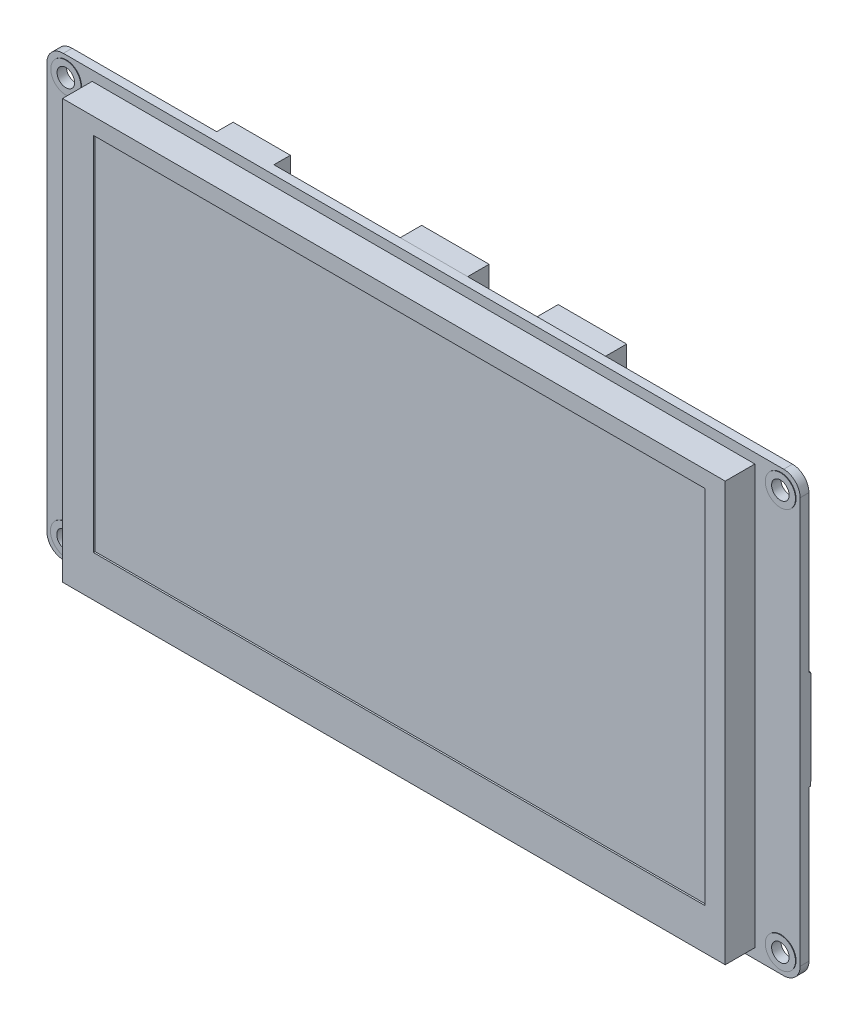
SolidWorks part; units mm, degrees
material "Plastique personnalisé"
ref_plane "Plan de face" through (0, 0, 0) normal (0, 0, 1) x (1, 0, 0)
ref_plane "Plan de dessus" through (0, 0, 0) normal (0, 1, 0) x (1, 0, 0)
ref_plane "Plan de droite" through (0, 0, 0) normal (1, 0, 0) x (0, 0, -1)
sketch "Esquisse1" plane through (0, 0, 0) normal (0, 0, 1) x (1, 0, 0)
  line L1 (-65.6, -39.95) -> (65.6, -39.95)
  line L2 (-68.6, -36.95) -> (-68.6, 36.95)
  line L3 (-65.6, 39.95) -> (65.6, 39.95)
  line L4 (68.6, -36.95) -> (68.6, 36.95)
  line L5 (-68.6, -39.95) -> (68.6, 39.95) construction
  line L6 (-68.6, 39.95) -> (68.6, -39.95) construction
  line L11 (-65.1, -36.45) -> (65.1, 36.45) construction
  line L12 (-65.1, 36.45) -> (65.1, -36.45) construction
  arc A0 (-68.6, 36.95) -> (-65.6, 39.95) centre (-65.6, 36.95) cw
  arc A1 (-65.6, -39.95) -> (-68.6, -36.95) centre (-65.6, -36.95) cw
  arc A2 (65.6, -39.95) -> (68.6, -36.95) centre (65.6, -36.95) ccw
  arc A3 (65.6, 39.95) -> (68.6, 36.95) centre (65.6, 36.95) cw
  circle A4 centre (-65.043, 36.45) radius 1.6
  circle A5 centre (65.1, 36.45) radius 1.6
  circle A6 centre (65.1, -36.45) radius 1.6
  circle A7 centre (-65.1, -36.45) radius 1.6
  point P0 (0, 0)
  point P18 (0, 0)
  dimension "D3" = 3
  dimension "D6" = 3.2
  dimension "D7" = 3.2
  dimension "D8" = 3.2
  dimension "D1" = 137.2
  dimension "D2" = 79.9
  dimension "D4" = 130.2
  dimension "D5" = 72.9
sketch "dalle ecran" plane through (0, 0, 0) normal (0, 0, 1) x (1, 0, 0)
  line L1 (-60.35, -38.15) -> (60.35, -38.15)
  line L2 (-60.35, -38.15) -> (-60.35, 38.15)
  line L3 (-60.35, 38.15) -> (60.35, 38.15)
  line L4 (60.35, -38.15) -> (60.35, 38.15)
  line L5 (-60.35, -38.15) -> (60.35, 38.15) construction
  line L6 (-60.35, 38.15) -> (60.35, -38.15) construction
  point P0 (0, 0)
  dimension "D1" = 120.7
  dimension "D2" = 76.3
extrude "Boss.-Extru.1" add sketch "Esquisse1" against normal blind 1.6
sketch "Esquisse4" plane through (0, 0, 0) normal (0, 0, 1) x (1, 0, 0)
  circle A0 centre (-65.043, 36.45) radius 1.6
  circle A1 centre (-65.043, 36.45) radius 2.7455
  circle A2 centre (65.1, 36.45) radius 1.6
  circle A3 centre (65.1, 36.45) radius 2.7533
  circle A4 centre (-65.1, -36.45) radius 1.6
  circle A5 centre (-65.1, -36.45) radius 2.7486
  circle A7 centre (65.1, -36.45) radius 2.7491
  circle A8 centre (65.1, -36.45) radius 1.6
extrude "Boss.-Extru.2" add sketch "Esquisse4" along normal blind 0.1
extrude "Boss.-Extru.3" add sketch "dalle ecran" along normal blind 5.4
sketch "Esquisse5" plane through (0, 0, 5.4) normal (0, 0, 1) x (1, 0, 0)
  line L0 (-60.35, 0) -> (-54.7003, 0) construction
  line L1 (-60.35, 38.15) -> (-60.35, -38.15) construction
  line L2 (0, -38.15) -> (0, -30.6518) construction
  line L3 (-60.35, -38.15) -> (60.35, -38.15) construction
  line L4 (0, -30.6518) -> (-54.7003, -30.6518) construction
  line L5 (0, 38.15) -> (0, 35.148) construction
  line L6 (60.35, 38.15) -> (-60.35, 38.15) construction
  line L7 (0, 35.148) -> (-54.7003, 35.148) construction
  line L8 (-54.7003, 0) -> (60.35, 0) construction
  line L9 (60.35, -38.15) -> (60.35, 38.15) construction
  line L10 (60.35, 0) -> (56.695, 0) construction
  line L11 (56.695, 0) -> (56.695, 35.148) construction
  line L13 (56.695, 35.148) -> (-54.7003, 35.148)
  line L14 (56.695, 35.148) -> (56.695, -30.6518)
  line L15 (56.695, -30.6518) -> (-54.7003, -30.6518)
  line L16 (-54.7003, 35.148) -> (-54.7003, -30.6518)
  dimension "D1" = 5.6497
extrude "Enlèv. mat.-Extru.1" cut sketch "Esquisse5" against normal blind 0.3
sketch "sd-card" plane through (0, 0, -1.6) normal (0, 0, -1) x (-1, 0, 0)
  line L0 (0, 0) -> (68.6, 0) construction
  line L1 (68.6, 36.95) -> (68.6, -36.95) construction
  line L2 (126.6709, 304.2897) -> (905.3376, 304.2897) construction
  line L4 (39.2733, -25.2253) -> (54.2505, -25.2253)
  line L5 (39.2733, -25.2253) -> (39.2733, -39.1139)
  line L6 (39.2733, -39.1139) -> (54.2505, -39.1139)
  line L7 (54.2505, -25.2253) -> (54.2505, -39.1139)
sketch "embase esp32S3" plane through (0, 0, -1.6) normal (0, 0, -1) x (-1, 0, 0)
  line L0 (-68.6, -36.95) -> (-68.6, 36.95) construction
  line L1 (-68.6, 8.5181) -> (-61.4864, 8.5181)
  line L2 (-68.6, 8.5181) -> (-68.6, -9.4826)
  line L3 (-68.6, -9.4826) -> (-61.3564, -9.4826)
  line L4 (-42.8193, 8.5181) -> (-42.8193, 6.945)
  line L5 (-60.2164, 9.3816) -> (-60.2164, 8.5181)
  line L6 (-61.4864, 9.3816) -> (-60.4586, 9.3816)
  line L7 (-61.4864, 9.3816) -> (-61.4864, 8.5181)
  line L9 (-60.4586, 9.3816) -> (-60.4586, 8.5181)
  line L10 (-60.2164, 9.3816) -> (-59.1886, 9.3816)
  line L11 (-59.1886, 9.3816) -> (-59.1886, 8.5181)
  line L13 (-58.9464, 9.3816) -> (-58.9464, 8.5181)
  line L14 (-58.9464, 9.3816) -> (-57.9186, 9.3816)
  line L15 (-57.9186, 9.3816) -> (-57.9186, 8.5181)
  line L17 (-57.6764, 9.3816) -> (-57.6764, 8.5181)
  line L18 (-57.6764, 9.3816) -> (-56.6486, 9.3816)
  line L19 (-56.6486, 9.3816) -> (-56.6486, 8.5181)
  line L21 (-56.4064, 9.3816) -> (-56.4064, 8.5181)
  line L22 (-56.4064, 9.3816) -> (-55.3786, 9.3816)
  line L23 (-55.3786, 9.3816) -> (-55.3786, 8.5181)
  line L25 (-55.1364, 9.3816) -> (-55.1364, 8.5181)
  line L26 (-55.1364, 9.3816) -> (-54.1086, 9.3816)
  line L27 (-54.1086, 9.3816) -> (-54.1086, 8.5181)
  line L29 (-53.8664, 9.3816) -> (-53.8664, 8.5181)
  line L30 (-53.8664, 9.3816) -> (-52.8386, 9.3816)
  line L31 (-52.8386, 9.3816) -> (-52.8386, 8.5181)
  line L33 (-52.5964, 9.3816) -> (-52.5964, 8.5181)
  line L34 (-52.5964, 9.3816) -> (-51.5686, 9.3816)
  line L35 (-51.5686, 9.3816) -> (-51.5686, 8.5181)
  line L37 (-51.3264, 9.3816) -> (-51.3264, 8.5181)
  line L38 (-51.3264, 9.3816) -> (-50.2986, 9.3816)
  line L39 (-50.2986, 9.3816) -> (-50.2986, 8.5181)
  line L41 (-50.0564, 9.3816) -> (-50.0564, 8.5181)
  line L42 (-50.0564, 9.3816) -> (-49.0286, 9.3816)
  line L43 (-49.0286, 9.3816) -> (-49.0286, 8.5181)
  line L45 (-48.7864, 9.3816) -> (-48.7864, 8.5181)
  line L46 (-48.7864, 9.3816) -> (-47.7586, 9.3816)
  line L47 (-47.7586, 9.3816) -> (-47.7586, 8.5181)
  line L49 (-47.5164, 9.3816) -> (-47.5164, 8.5181)
  line L50 (-47.5164, 9.3816) -> (-46.4886, 9.3816)
  line L51 (-46.4886, 9.3816) -> (-46.4886, 8.5181)
  line L53 (-46.2464, 9.3816) -> (-46.2464, 8.5181)
  line L54 (-46.2464, 9.3816) -> (-45.2186, 9.3816)
  line L55 (-45.2186, 9.3816) -> (-45.2186, 8.5181)
  line L57 (-44.9764, 9.3816) -> (-44.9764, 8.5181)
  line L58 (-44.9764, 9.3816) -> (-43.9486, 9.3816)
  line L59 (-43.9486, 9.3816) -> (-43.9486, 8.5181)
  line L61 (-60.4586, 8.5181) -> (-60.2164, 8.5181)
  line L62 (-59.1886, 8.5181) -> (-58.9464, 8.5181)
  line L63 (-57.9186, 8.5181) -> (-57.6764, 8.5181)
  line L64 (-56.6486, 8.5181) -> (-56.4064, 8.5181)
  line L65 (-55.3786, 8.5181) -> (-55.1364, 8.5181)
  line L66 (-54.1086, 8.5181) -> (-53.8664, 8.5181)
  line L67 (-52.8386, 8.5181) -> (-52.5964, 8.5181)
  line L68 (-51.5686, 8.5181) -> (-51.3264, 8.5181)
  line L69 (-50.2986, 8.5181) -> (-50.0564, 8.5181)
  line L70 (-49.0286, 8.5181) -> (-48.7864, 8.5181)
  line L71 (-47.7586, 8.5181) -> (-47.5164, 8.5181)
  line L72 (-46.4886, 8.5181) -> (-46.2464, 8.5181)
  line L73 (-45.2186, 8.5181) -> (-44.9764, 8.5181)
  line L74 (-43.9486, 8.5181) -> (-42.8193, 8.5181)
  line L88 (-42.8193, 5.675) -> (-42.0215, 5.675)
  line L89 (-42.8193, 6.945) -> (-42.0215, 6.945)
  line L91 (-42.8193, 6.1624) -> (-42.0215, 6.1624)
  line L92 (-42.0215, 6.945) -> (-42.0215, 6.1624)
  line L93 (-42.0215, 5.675) -> (-42.0215, 4.8924)
  line L94 (-42.8193, 4.8924) -> (-42.0215, 4.8924)
  line L96 (-42.8193, 4.405) -> (-42.0215, 4.405)
  line L97 (-42.0215, 4.405) -> (-42.0215, 3.6224)
  line L98 (-42.8193, 3.6224) -> (-42.0215, 3.6224)
  line L100 (-42.8193, 3.135) -> (-42.0215, 3.135)
  line L101 (-42.0215, 3.135) -> (-42.0215, 2.3524)
  line L102 (-42.8193, 2.3524) -> (-42.0215, 2.3524)
  line L104 (-42.8193, 1.865) -> (-42.0215, 1.865)
  line L105 (-42.0215, 1.865) -> (-42.0215, 1.0824)
  line L106 (-42.8193, 1.0824) -> (-42.0215, 1.0824)
  line L108 (-42.8193, 0.595) -> (-42.0215, 0.595)
  line L109 (-42.0215, 0.595) -> (-42.0215, -0.1876)
  line L110 (-42.8193, -0.1876) -> (-42.0215, -0.1876)
  line L112 (-42.8193, -0.675) -> (-42.0215, -0.675)
  line L113 (-42.0215, -0.675) -> (-42.0215, -1.4576)
  line L114 (-42.8193, -1.4576) -> (-42.0215, -1.4576)
  line L116 (-42.8193, -1.945) -> (-42.0215, -1.945)
  line L117 (-42.0215, -1.945) -> (-42.0215, -2.7276)
  line L118 (-42.8193, -2.7276) -> (-42.0215, -2.7276)
  line L120 (-42.8193, -3.215) -> (-42.0215, -3.215)
  line L121 (-42.0215, -3.215) -> (-42.0215, -3.9976)
  line L122 (-42.8193, -3.9976) -> (-42.0215, -3.9976)
  line L124 (-42.8193, -4.485) -> (-42.0215, -4.485)
  line L125 (-42.0215, -4.485) -> (-42.0215, -5.2676)
  line L126 (-42.8193, -5.2676) -> (-42.0215, -5.2676)
  line L128 (-42.8193, -5.755) -> (-42.0215, -5.755)
  line L129 (-42.0215, -5.755) -> (-42.0215, -6.5376)
  line L130 (-42.8193, -6.5376) -> (-42.0215, -6.5376)
  line L132 (-42.8193, -7.025) -> (-42.0215, -7.025)
  line L133 (-42.0215, -7.025) -> (-42.0215, -7.8076)
  line L134 (-42.8193, -7.8076) -> (-42.0215, -7.8076)
  line L136 (-42.8193, 6.1624) -> (-42.8193, 5.675)
  line L137 (-42.8193, 4.8924) -> (-42.8193, 4.405)
  line L138 (-42.8193, 3.6224) -> (-42.8193, 3.135)
  line L139 (-42.8193, 2.3524) -> (-42.8193, 1.865)
  line L140 (-42.8193, 1.0824) -> (-42.8193, 0.595)
  line L141 (-42.8193, -0.1876) -> (-42.8193, -0.675)
  line L142 (-42.8193, -1.4576) -> (-42.8193, -1.945)
  line L143 (-42.8193, -2.7276) -> (-42.8193, -3.215)
  line L144 (-42.8193, -3.9976) -> (-42.8193, -4.485)
  line L145 (-42.8193, -5.2676) -> (-42.8193, -5.755)
  line L146 (-42.8193, -6.5376) -> (-42.8193, -7.025)
  line L147 (-42.8193, -7.8076) -> (-42.8193, -9.4826)
  line L148 (-46.1164, -9.4826) -> (-46.1164, -10.3789)
  line L150 (-44.8464, -9.4826) -> (-44.8464, -10.3789)
  line L151 (-44.8464, -10.3789) -> (-43.9768, -10.3789)
  line L152 (-43.9768, -9.4826) -> (-43.9768, -10.3789)
  line L154 (-45.2468, -9.4826) -> (-45.2468, -10.3789)
  line L155 (-46.1164, -10.3789) -> (-45.2468, -10.3789)
  line L156 (-47.3864, -9.4826) -> (-47.3864, -10.3789)
  line L158 (-46.5168, -9.4826) -> (-46.5168, -10.3789)
  line L159 (-47.3864, -10.3789) -> (-46.5168, -10.3789)
  line L160 (-48.6564, -9.4826) -> (-48.6564, -10.3789)
  line L161 (-48.6564, -9.4826) -> (-47.7868, -9.4826)
  line L162 (-47.7868, -9.4826) -> (-47.7868, -10.3789)
  line L163 (-48.6564, -10.3789) -> (-47.7868, -10.3789)
  line L164 (-49.9264, -9.4826) -> (-49.9264, -10.3789)
  line L166 (-49.0568, -9.4826) -> (-49.0568, -10.3789)
  line L167 (-49.9264, -10.3789) -> (-49.0568, -10.3789)
  line L168 (-51.1964, -9.4826) -> (-51.1964, -10.3789)
  line L170 (-50.3268, -9.4826) -> (-50.3268, -10.3789)
  line L171 (-51.1964, -10.3789) -> (-50.3268, -10.3789)
  line L172 (-52.4664, -9.4826) -> (-52.4664, -10.3789)
  line L174 (-51.5968, -9.4826) -> (-51.5968, -10.3789)
  line L175 (-52.4664, -10.3789) -> (-51.5968, -10.3789)
  line L176 (-53.7364, -9.4826) -> (-53.7364, -10.3789)
  line L178 (-52.8668, -9.4826) -> (-52.8668, -10.3789)
  line L179 (-53.7364, -10.3789) -> (-52.8668, -10.3789)
  line L180 (-55.0064, -9.4826) -> (-55.0064, -10.3789)
  line L182 (-54.1368, -9.4826) -> (-54.1368, -10.3789)
  line L183 (-55.0064, -10.3789) -> (-54.1368, -10.3789)
  line L184 (-56.2764, -9.4826) -> (-56.2764, -10.3789)
  line L186 (-55.4068, -9.4826) -> (-55.4068, -10.3789)
  line L187 (-56.2764, -10.3789) -> (-55.4068, -10.3789)
  line L188 (-57.5464, -9.4826) -> (-57.5464, -10.3789)
  line L190 (-56.6768, -9.4826) -> (-56.6768, -10.3789)
  line L191 (-57.5464, -10.3789) -> (-56.6768, -10.3789)
  line L192 (-58.8164, -9.4826) -> (-58.8164, -10.3789)
  line L194 (-57.9468, -9.4826) -> (-57.9468, -10.3789)
  line L195 (-58.8164, -10.3789) -> (-57.9468, -10.3789)
  line L196 (-60.0864, -9.4826) -> (-60.0864, -10.3789)
  line L198 (-59.2168, -9.4826) -> (-59.2168, -10.3789)
  line L199 (-60.0864, -10.3789) -> (-59.2168, -10.3789)
  line L200 (-61.3564, -9.4826) -> (-61.3564, -10.3789)
  line L202 (-60.4868, -9.4826) -> (-60.4868, -10.3789)
  line L203 (-61.3564, -10.3789) -> (-60.4868, -10.3789)
  line L204 (-60.4868, -9.4826) -> (-60.0864, -9.4826)
  line L207 (-59.2168, -9.4826) -> (-58.8164, -9.4826)
  line L209 (-57.9468, -9.4826) -> (-57.5464, -9.4826)
  line L211 (-56.6768, -9.4826) -> (-56.2764, -9.4826)
  line L213 (-55.4068, -9.4826) -> (-55.0064, -9.4826)
  line L215 (-54.1368, -9.4826) -> (-53.7364, -9.4826)
  line L217 (-52.8668, -9.4826) -> (-52.4664, -9.4826)
  line L219 (-51.5968, -9.4826) -> (-51.1964, -9.4826)
  line L221 (-50.3268, -9.4826) -> (-49.9264, -9.4826)
  line L223 (-49.0568, -9.4826) -> (-47.3864, -9.4826)
  line L225 (-46.5168, -9.4826) -> (-46.1164, -9.4826)
  line L227 (-45.2468, -9.4826) -> (-44.8464, -9.4826)
  line L228 (-43.9768, -9.4826) -> (-42.8193, -9.4826)
  dimension "D1" = 14
  dimension "D2" = 12
  dimension "D3" = 14
sketch "corps esp32S3" plane through (0, 0, 0) normal (0, 0, 1) x (1, 0, 0)
  line L0 (68.6, 8.5181) -> (68.6, -9.4826) construction
  line L1 (68.6, 8.2493) -> (43.4421, 8.2493)
  line L2 (68.6, 8.2493) -> (68.6, -8.7891)
  line L3 (68.6, -8.7891) -> (43.4421, -8.7891)
  line L4 (43.4421, 8.2493) -> (43.4421, -8.7891)
sketch "blindage esp32" plane through (0, 0, 0) normal (0, 0, 1) x (1, 0, 0)
  line L1 (61.8693, 7.5456) -> (44.219, 7.5456)
  line L2 (61.8693, 7.5456) -> (61.8693, -7.9838)
  line L3 (61.8693, -7.9838) -> (44.219, -7.9838)
  line L4 (44.219, 7.5456) -> (44.219, -7.9838)
sketch "JST Stuff" plane through (0, 0, 0) normal (0, 0, 1) x (1, 0, 0)
  line L0 (65.6, 39.95) -> (-65.6, 39.95) construction
  line L1 (31.3996, 39.7927) -> (18.9353, 39.7927)
  line L2 (31.3996, 39.7927) -> (31.3996, 32.4743)
  line L3 (31.3996, 32.4743) -> (18.9353, 32.4743)
  line L4 (18.9353, 39.7927) -> (18.9353, 32.4743)
  line L5 (6.344, 39.95) -> (-5.9396, 39.95)
  line L6 (6.344, 39.95) -> (6.344, 32.4743)
  line L7 (6.344, 32.4743) -> (-5.9396, 32.4743)
  line L8 (-5.9396, 39.95) -> (-5.9396, 32.4743)
  line L9 (-65.6, -39.95) -> (65.6, -39.95) construction
  line L10 (-67.8265, -16.1957) -> (-62.0375, -16.1957)
  line L11 (-67.8265, -16.1957) -> (-67.8265, -24.5296)
  line L12 (-67.8265, -24.5296) -> (-62.0375, -24.5296)
  line L13 (-62.0375, -16.1957) -> (-62.0375, -24.5296)
  line L14 (52.1633, -33.8675) -> (43.6832, -33.8675)
  line L15 (52.1633, -33.8675) -> (52.1633, -39.95)
  line L16 (52.1633, -39.95) -> (43.6832, -39.95)
  line L17 (43.6832, -33.8675) -> (43.6832, -39.95)
sketch "usb and black" plane through (0, 0, 0) normal (0, 0, 1) x (1, 0, 0)
  line L0 (-68.6, 36.95) -> (-68.6, -36.95) construction
  line L1 (-68.6, 3.7115) -> (-61.2568, 3.7115)
  line L2 (-68.6, 3.7115) -> (-68.6, -4.5437)
  line L3 (-68.6, -4.5437) -> (-61.2568, -4.5437)
  line L4 (-61.2568, 3.7115) -> (-61.2568, -4.5437)
  line L5 (65.6, 39.95) -> (-65.6, 39.95) construction
  line L6 (-28.846, 39.95) -> (-39.277, 39.95)
  line L7 (-28.846, 39.95) -> (-28.846, 31.1276)
  line L8 (-28.846, 31.1276) -> (-39.277, 31.1276)
  line L9 (-39.277, 39.95) -> (-39.277, 31.1276)
sketch "cncteurs nappes" plane through (0, 0, 0) normal (0, 0, 1) x (1, 0, 0)
  line L1 (29.8687, -5.1591) -> (21.4014, -5.1591)
  line L2 (29.8687, -5.1591) -> (29.8687, -10.1637)
  line L3 (29.8687, -10.1637) -> (21.4014, -10.1637)
  line L4 (21.4014, -5.1591) -> (21.4014, -10.1637)
  line L5 (-12.3555, 7.8002) -> (-35.8239, 7.8002)
  line L6 (-12.3555, 7.8002) -> (-12.3555, 2.9753)
  line L7 (-12.3555, 2.9753) -> (-35.8239, 2.9753)
  line L8 (-35.8239, 7.8002) -> (-35.8239, 2.9753)
extrude "Boss.-Extru.6" add sketch "cncteurs nappes" against normal blind 1.95
extrude "Boss.-Extru.7" add sketch "usb and black" against normal blind 4.6
fillet "Congé1" radius 1.5 2 edges at (-64.9284, 3.7115, -4.6) (-64.9284, -4.5437, -4.6)
sketch "Esquisse13" plane through (-68.6, 0, 0) normal (-1, 0, 0) x (0, 0, 1)
  line L1 (-3.4059, -3.747) -> (-2.3114, -3.747)
  line L2 (-3.9059, -3.247) -> (-3.9059, 2.3843)
  line L3 (-3.4059, 2.8843) -> (-2.3114, 2.8843)
  line L4 (-1.8114, -3.247) -> (-1.8114, 2.3843)
  line L5 (-3.9059, -3.747) -> (-1.8114, 2.8843) construction
  line L6 (-3.9059, 2.8843) -> (-1.8114, -3.747) construction
  arc A0 (-2.3114, -3.747) -> (-1.8114, -3.247) centre (-2.3114, -3.247) ccw
  arc A1 (-3.4059, -3.747) -> (-3.9059, -3.247) centre (-3.4059, -3.247) cw
  arc A2 (-3.9059, 2.3843) -> (-3.4059, 2.8843) centre (-3.4059, 2.3843) cw
  arc A3 (-2.3114, 2.8843) -> (-1.8114, 2.3843) centre (-2.3114, 2.3843) cw
  point P0 (-2.8586, -0.4313)
  dimension "D1" = 0.5
extrude "Enlèv. mat.-Extru.2" cut sketch "Esquisse13" against normal blind 6.6
extrude "Boss.-Extru.8" add sketch "sd-card" along normal blind 1.87
sketch "Esquisse14" plane through (0, -39.1139, 0) normal (0, -1, 0) x (1, 0, 0)
  line L1 (-53.7635, -3.0279) -> (-39.9094, -3.0279)
  line L2 (-53.7635, -3.0279) -> (-53.7635, -1.9496)
  line L3 (-53.7635, -1.9496) -> (-39.9094, -1.9496)
  line L4 (-39.9094, -3.0279) -> (-39.9094, -1.9496)
  line L5 (-53.7635, -3.0279) -> (-39.9094, -1.9496) construction
  line L6 (-53.7635, -1.9496) -> (-39.9094, -3.0279) construction
  point P0 (-46.8364, -2.4887)
extrude "Enlèv. mat.-Extru.3" cut sketch "Esquisse14" against normal blind 11.87
extrude "Boss.-Extru.9" add sketch "JST Stuff" against normal blind 5.6
extrude "Boss.-Extru.10" add sketch "embase esp32S3" along normal blind 0.3 contours L152 L228 L147 L134 L133 L132 L146 L130 L129 L128 L145 L126 L125 L124 L144 L122 L121 L120 L143 L118 L117 L116 L142 L114 L113 L112 L141 L110 L109 L108 L140 L106 L105 L104 L139 L102 L101 L100 L138 L98 L97 L96 L137 L94 L93 L88 L136 L91 L92 L89 L4
extrude "Boss.-Extru.11" add sketch "corps esp32S3" against normal blind 2
extrude "Boss.-Extru.12" add sketch "blindage esp32" against normal blind 4.6
sketch "Esquisse15" plane through (-68.6, 0, 0) normal (-1, 0, 0) x (0, 0, 1)
  line L1 (-1.6, -4.5437) -> (-5.3445, -4.5437)
  line L2 (-1.6, -4.5437) -> (-1.6, 3.7399)
  line L3 (-1.6, 3.7399) -> (-5.3445, 3.7399)
  line L4 (-5.3445, -4.5437) -> (-5.3445, 3.7399)
extrude "Enlèv. mat.-Extru.4" cut sketch "Esquisse15" against normal blind 0.1
sketch "Esquisse16" plane through (0, 39.95, 0) normal (0, 1, 0) x (1, 0, 0)
  line L1 (-5.9396, 5.6) -> (6.344, 5.6)
  line L2 (-5.9396, 5.6) -> (-5.9396, 1.6)
  line L3 (-5.9396, 1.6) -> (6.344, 1.6)
  line L4 (6.344, 5.6) -> (6.344, 1.6)
extrude "Enlèv. mat.-Extru.5" cut sketch "Esquisse16" against normal blind 0.1
sketch "Esquisse17" plane through (0, -39.95, 0) normal (0, -1, 0) x (1, 0, 0)
  line L1 (43.6832, -5.6) -> (52.1633, -5.6)
  line L2 (43.6832, -5.6) -> (43.6832, -1.6)
  line L3 (43.6832, -1.6) -> (52.1633, -1.6)
  line L4 (52.1633, -5.6) -> (52.1633, -1.6)
extrude "Enlèv. mat.-Extru.6" cut sketch "Esquisse17" against normal blind 0.1
